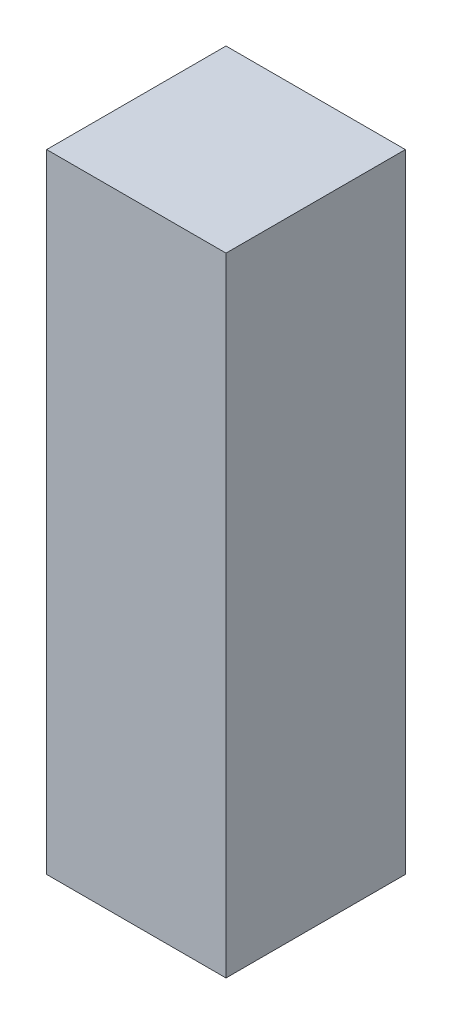
SolidWorks part; units mm, degrees
ref_plane "Front Plane" through (0, 0, 0) normal (0, 0, 1) x (1, 0, 0)
ref_plane "Top Plane" through (0, 0, 0) normal (0, 1, 0) x (1, 0, 0)
ref_plane "Right Plane" through (0, 0, 0) normal (1, 0, 0) x (0, 0, -1)
sketch "Sketch1" plane through (0, 0, 0) normal (0, 1, 0) x (1, 0, 0)
  line L1 (-12.7, -12.7) -> (12.7, -12.7)
  line L2 (-12.7, -12.7) -> (-12.7, 12.7)
  line L3 (-12.7, 12.7) -> (12.7, 12.7)
  line L4 (12.7, -12.7) -> (12.7, 12.7)
  line L5 (-12.7, -12.7) -> (12.7, 12.7) construction
  line L6 (-12.7, 12.7) -> (12.7, -12.7) construction
  point P0 (0, 0)
  dimension "D1" = 25.4
extrude "Boss-Extrude1" add sketch "Sketch1" along normal mid plane 88.9
